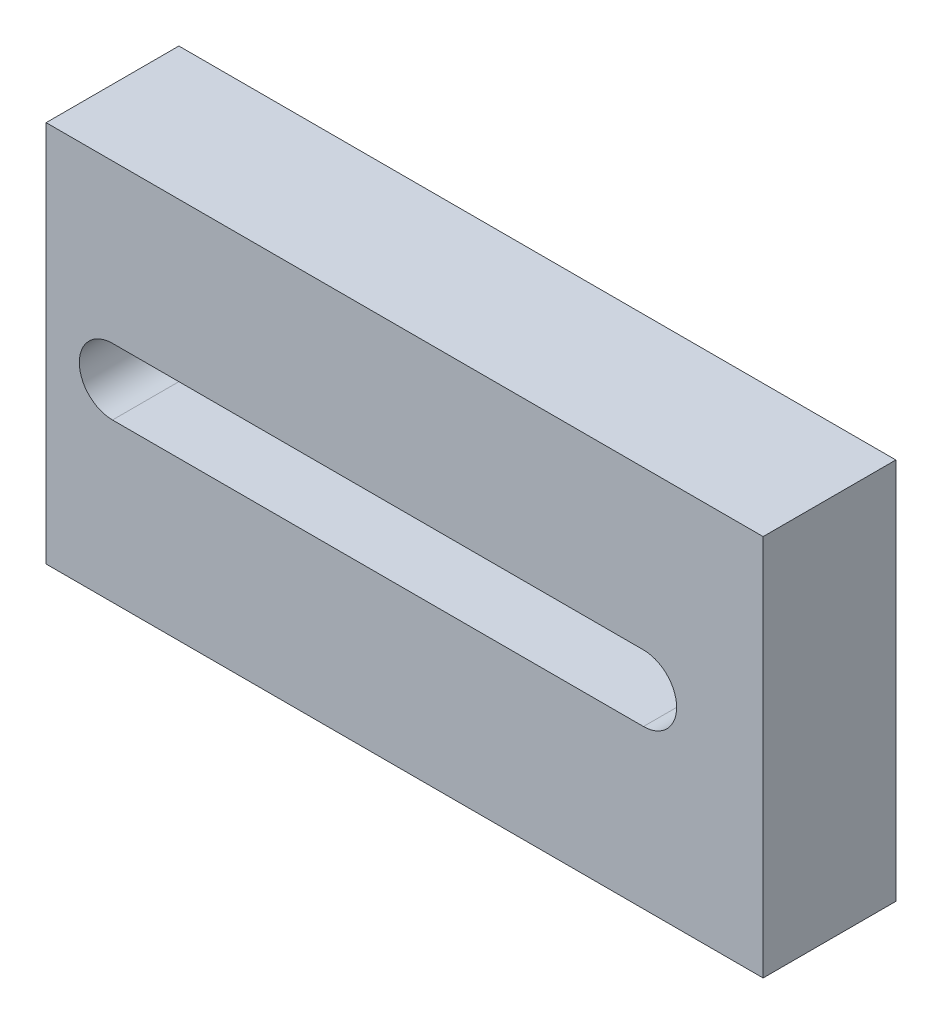
SolidWorks part; units mm, degrees
ref_plane "Front Plane" through (0, 0, 0) normal (0, 0, 1) x (1, 0, 0)
ref_plane "Top Plane" through (0, 0, 0) normal (0, 1, 0) x (1, 0, 0)
ref_plane "Right Plane" through (0, 0, 0) normal (1, 0, 0) x (0, 0, -1)
sketch "Sketch1" plane through (0, 0, 0) normal (0, 0, 1) x (1, 0, 0)
  line L0 (6576.9631, 3585.7578) -> (6611.2633, 3585.7578)
  line L1 (6576.9631, 3567.4696) -> (6576.9631, 3585.7578)
  line L2 (6580.1381, 3578.2012) -> (6605.5381, 3578.2012)
  line L3 (6580.1381, 3575.0262) -> (6605.5381, 3575.0262)
  line L4 (6611.2633, 3567.4696) -> (6611.2633, 3585.7578)
  line L5 (6576.9631, 3567.4696) -> (6611.2633, 3567.4696)
  arc A0 (6580.1381, 3578.2012) -> (6580.1381, 3575.0262) centre (6580.1381, 3576.6137) ccw
  arc A1 (6605.5381, 3575.0262) -> (6605.5381, 3578.2012) centre (6605.5381, 3576.6137) ccw
extrude "Boss-Extrude1" add sketch "Sketch1" along normal blind 6.35
